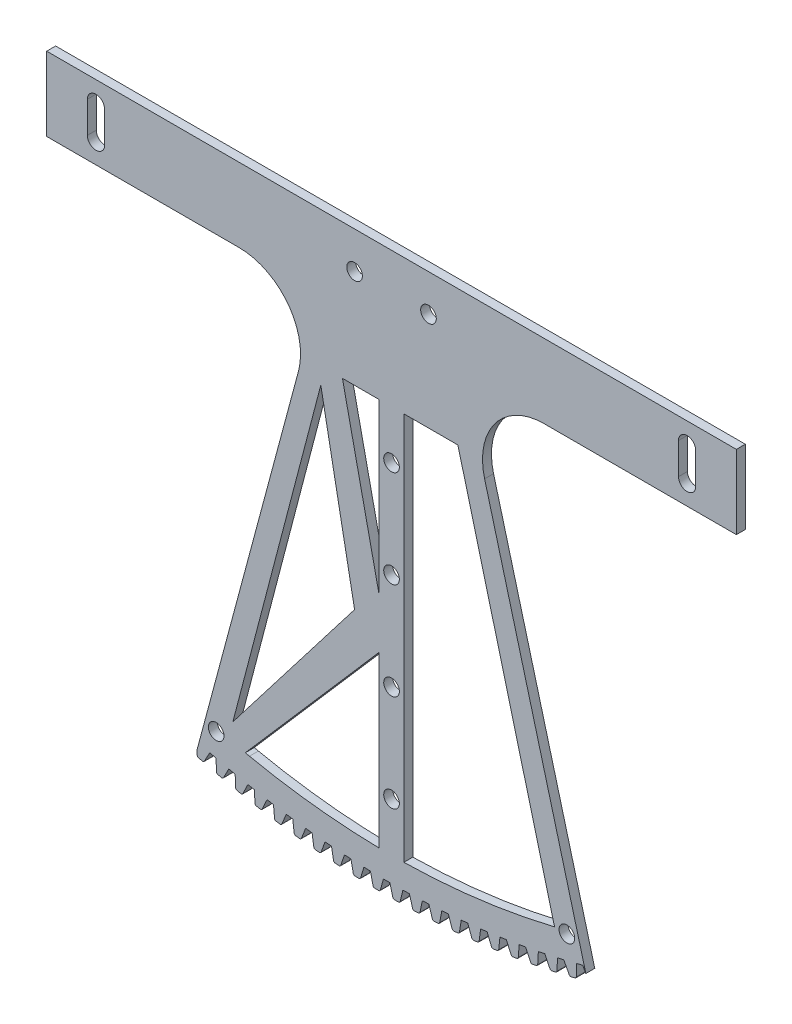
SolidWorks part; units mm, degrees
material "201 Annealed Stainless Steel (SS)"
ref_plane "Front Plane" through (0, 0, 0) normal (0, 0, 1) x (1, 0, 0)
ref_plane "Top Plane" through (0, 0, 0) normal (0, 1, 0) x (1, 0, 0)
ref_plane "Right Plane" through (0, 0, 0) normal (1, 0, 0) x (0, 0, -1)
sketch "Sketch3" plane through (0, 0, 0) normal (0, 0, 1) x (1, 0, 0)
  line L0 (0, 0) -> (0, -304.8) construction
  line L1 (-21.234, -79.2464) -> (-78.888, -294.4142)
  line L2 (21.234, -79.2464) -> (78.888, -294.4142)
  line L4 (-140, -79.56) -> (140, -79.56)
  line L5 (-140, -79.56) -> (-140, -109.56)
  line L6 (-140, -109.56) -> (140, -109.56)
  line L7 (140, -79.56) -> (140, -109.56)
  line L8 (0, -109.56) -> (0, -79.56) construction
  line L9 (-140, -94.56) -> (140, -94.56) construction
  arc A0 (-78.888, -294.4142) -> (78.888, -294.4142) centre (0, 0) ccw
  point P269 (0, -94.56)
  dimension "D1" = 304.8
  dimension "D4" = 79.56
  dimension "D5" = 30
  dimension "D6" = 280
  dimension "D7" = 140
extrude "Boss-Extrude2" add sketch "Sketch3" along normal blind 3.6286 contours L7 L4 L2 L6 | L1 L6 L2 L4 | L1 L4 L2 | L5 L6 L1 L4 | L1 A0 L2 L6
fillet "Fillet1" radius 25 2 edges at (-29.3565, -109.56, 1.8143) (29.3565, -109.56, 1.8143)
sketch "Sketch4" plane through (0, -79.56, 0) normal (0, 1, 0) x (1, 0, 0)
  line L1 (-140, 0) -> (140, 0)
  line L2 (-140, 0) -> (-140, -3.6286)
  line L3 (-140, -3.6286) -> (140, -3.6286)
  line L4 (140, 0) -> (140, -3.6286)
  line L5 (0, -3.6286) -> (0, 0) construction
  line L6 (-140, -1.8143) -> (140, -1.8143) construction
  point P252 (0, -1.8143)
sketch "Sketch5" plane through (0, 0, 0) normal (0, 0, -1) x (-1, 0, 0)
  line L0 (-123.5, -94.56) -> (-123.5, -100.91)
  line L1 (-116.5, -94.56) -> (-116.5, -100.91)
  line L2 (116.5, -94.56) -> (116.5, -88.21)
  line L3 (140, -79.56) -> (-140, -79.56) construction
  line L4 (-120, -88.21) -> (-120, -100.91) construction
  line L5 (0, -79.56) -> (0, -109.56) construction
  line L6 (-116.5, -94.56) -> (-116.5, -88.21)
  line L7 (-123.5, -94.56) -> (-123.5, -88.21)
  line L8 (116.5, -94.56) -> (116.5, -100.91)
  line L9 (123.5, -94.56) -> (123.5, -100.91)
  line L10 (123.5, -94.56) -> (123.5, -88.21)
  line L11 (-140, -79.56) -> (-140, -109.56) construction
  line L12 (120, -88.21) -> (120, -100.91) construction
  arc A1 (-116.5, -88.21) -> (-123.5, -88.21) centre (-120, -88.21) ccw
  arc A2 (-123.5, -100.91) -> (-116.5, -100.91) centre (-120, -100.91) ccw
  arc A3 (123.5, -100.91) -> (116.5, -100.91) centre (120, -100.91) cw
  arc A4 (116.5, -88.21) -> (123.5, -88.21) centre (120, -88.21) cw
  circle A5 centre (-15, -94.56) radius 3.175
  circle A6 centre (15, -94.56) radius 3.175
  dimension "D1" = 16.5
  dimension "D2" = 7
  dimension "D3" = 8.65
  dimension "D5" = 3.5
  dimension "D6" = 15
  dimension "D8" = 6.35
  dimension "D4" = 6.35
  dimension "D7" = 15
sketch "Sketch13" plane through (0, 0, 0) normal (0, 0, -1) x (-1, 0, 0)
  line L0 (0, 0) -> (78.888, -294.4142)
  line L1 (0, 0) -> (-78.888, -294.4142)
  arc A0 (-78.888, -294.4142) -> (78.888, -294.4142) centre (0, 0) ccw
  arc A1 (-78.888, -294.4142) -> (78.888, -294.4142) centre (0, 0) ccw construction
  arc A2 (-78.888, -294.4142) -> (78.888, -294.4142) centre (0, 0) ccw
  circle A3 centre (0, 0) radius 304.8
  dimension "D1" = 609.6
sketch "Sketch14" plane through (0, 0, 0) normal (0, 0, -1) x (-1, 0, 0)
  line L0 (0, 0) -> (80.0203, -298.6399) construction
  line L2 (78.888, -294.4142) -> (78.9109, -297.0369)
  line L3 (78.9109, -297.0369) -> (76.2891, -297.7211)
  line L18 (76.2891, -297.7211) -> (75.0275, -295.4216)
  line L20 (0, 0) -> (-79.2746, -295.8555) construction
  line L32 (78.888, -294.4142) -> (75.0275, -295.4216)
  line L33 (75.0275, -295.4216) -> (78.888, -294.4142)
  line L34 (0, 0) -> (-75.3952, -296.8678) construction
  line L35 (0, 0) -> (-71.5028, -297.8293) construction
  line L36 (0, 0) -> (-67.5982, -298.7397) construction
  line L37 (0, 0) -> (-63.6821, -299.5989) construction
  line L38 (0, 0) -> (-59.755, -300.4068) construction
  line L39 (0, 0) -> (-55.8176, -301.1633) construction
  line L40 (0, 0) -> (-51.8707, -301.8681) construction
  line L41 (0, 0) -> (-47.9149, -302.5212) construction
  line L42 (0, 0) -> (-43.951, -303.1225) construction
  line L43 (0, 0) -> (-39.9794, -303.6718) construction
  line L44 (0, 0) -> (-36.0011, -304.1691) construction
  line L45 (0, 0) -> (-32.0165, -304.6143) construction
  line L46 (0, 0) -> (-28.0265, -305.0073) construction
  line L47 (0, 0) -> (-24.0316, -305.348) construction
  line L48 (0, 0) -> (-20.0327, -305.6364) construction
  line L49 (0, 0) -> (-16.0303, -305.8724) construction
  line L50 (0, 0) -> (-12.0252, -306.0561) construction
  line L51 (0, 0) -> (-8.018, -306.1873) construction
  line L52 (0, 0) -> (-4.0094, -306.266) construction
  line L53 (0, 0) -> (-0.0002, -306.2922) construction
  line L54 (0, 0) -> (4.0091, -306.266) construction
  line L55 (0, 0) -> (8.0176, -306.1873) construction
  line L56 (0, 0) -> (12.0248, -306.0561) construction
  line L57 (0, 0) -> (16.03, -305.8725) construction
  line L58 (0, 0) -> (20.0323, -305.6364) construction
  line L59 (0, 0) -> (24.0313, -305.348) construction
  line L60 (0, 0) -> (28.0261, -305.0073) construction
  line L61 (0, 0) -> (32.0162, -304.6143) construction
  line L62 (0, 0) -> (36.0007, -304.1691) construction
  line L63 (0, 0) -> (39.9791, -303.6719) construction
  line L64 (0, 0) -> (43.9506, -303.1225) construction
  line L65 (0, 0) -> (47.9146, -302.5213) construction
  line L66 (0, 0) -> (51.8704, -301.8682) construction
  line L67 (0, 0) -> (55.8173, -301.1633) construction
  line L68 (0, 0) -> (59.7546, -300.4069) construction
  line L69 (0, 0) -> (63.6817, -299.599) construction
  line L70 (0, 0) -> (67.5979, -298.7398) construction
  line L71 (0, 0) -> (71.5025, -297.8293) construction
  line L72 (0, 0) -> (75.3948, -296.8679) construction
  line L73 (0, 0) -> (-79.2746, -295.8555) construction
  line L74 (0, 0) -> (-75.3952, -296.8678) construction
  line L137 (37.789, -141.0305) -> (78.888, -294.4142) construction
  line L138 (-140, -79.56) -> (-140, -109.56)
  line L139 (-140, -109.56) -> (-61.9371, -109.56)
  line L140 (-37.789, -141.0305) -> (-78.888, -294.4142)
  line L141 (78.888, -294.4142) -> (37.789, -141.0305)
  line L142 (61.9371, -109.56) -> (140, -109.56)
  line L143 (140, -109.56) -> (140, -79.56)
  line L144 (140, -79.56) -> (-140, -79.56)
  line L145 (-140, -79.56) -> (-140, -109.56)
  line L146 (-140, -109.56) -> (-61.9371, -109.56)
  line L147 (-37.789, -141.0305) -> (-78.888, -294.4142)
  line L149 (61.9371, -109.56) -> (140, -109.56)
  line L150 (140, -109.56) -> (140, -79.56)
  line L151 (140, -79.56) -> (-140, -79.56)
  circle A0 centre (0, 0) radius 307.34
  circle A1 centre (0, 0) radius 302.26
  arc A3 (-37.789, -141.0305) -> (-61.9371, -109.56) centre (-61.9371, -134.56) ccw
  arc A5 (61.9371, -109.56) -> (37.789, -141.0305) centre (61.9371, -134.56) ccw
  arc A6 (-37.789, -141.0305) -> (-61.9371, -109.56) centre (-61.9371, -134.56) ccw
  arc A8 (61.9371, -109.56) -> (37.789, -141.0305) centre (61.9371, -134.56) ccw
  arc A11 (-78.888, -294.4142) -> (78.888, -294.4142) centre (0, 0) ccw
  arc A12 (-78.888, -294.4142) -> (78.888, -294.4142) centre (0, 0) ccw
  dimension "D5" = 614.68
  dimension "D6" = 30
  dimension "D7" = 40
  dimension "D4" = 604.52
  dimension "D1" = 14.5
  dimension "D3" = 14.5
  dimension "D8" = 0.75
  dimension "D9" = 306.2922
  dimension "D10" = 0.75
  dimension "D2" = 0
extrude "Boss-Extrude4" add sketch "Sketch14" against normal up to surface (3.6286 mm away) up to face at (0, -146.6727, 3.6286)
sketch "Sketch15" plane through (0, 0, 0) normal (1, 0, 0) x (0, 0, -1)
  line L0 (0, 0) -> (-23.3364, 0) construction
sketch "Sketch16" plane through (0, 0, 0) normal (0, 0, -1) x (-1, 0, 0)
  line L0 (75.0275, -295.4216) -> (73.7653, -293.1208)
  line L1 (73.7653, -293.1208) -> (71.1999, -293.7544)
  line L2 (71.1999, -293.7544) -> (71.1541, -296.3784)
  line L3 (0, 0) -> (71.5025, -297.8293) construction
  line L4 (0, 0) -> (75.3948, -296.8679) construction
  circle A0 centre (0, 0) radius 302.26 construction
  arc A1 (-78.888, -294.4142) -> (78.888, -294.4142) centre (0, 0) ccw construction
  dimension "D1" = 14.5
  dimension "D2" = 14.5
extrude "Cut-Extrude2" cut sketch "Sketch16" against normal through all and the other way through all
fillet "Fillet2" radius 0.7 2 edges at (-76.2891, -297.7211, 1.8143) (-78.9109, -297.0369, 1.8143)
pattern_circular "CirPattern8" count 20 every 1.5 about axis through (0, 0, 0) along (0, 0, 1) of "Cut-Extrude2", "Boss-Extrude4", "Fillet2"
extrude "Cut-Extrude3" cut sketch "Sketch5" against normal through all
sketch "Sketch17" plane through (0, 0, 0) normal (0, 0, -1) x (-1, 0, 0)
  line L0 (0, -79.56) -> (0, -134.56) construction
  line L1 (140, -79.56) -> (-140, -79.56) construction
  line L2 (-61.9371, -109.56) -> (61.9371, -109.56) construction
  line L3 (-36.9371, -134.56) -> (-26.9371, -134.56) construction
  line L4 (-36.9371, -134.56) -> (-26.9371, -134.56) construction
  line L5 (-26.9371, -134.56) -> (-66.1944, -284.3612) construction
  line L6 (-66.1944, -284.3612) -> (-76.1944, -284.3612) construction
  line L7 (0, -292.2593) -> (5, -292.2593) construction
  line L8 (-37.789, -141.0305) -> (-78.888, -294.4142) construction
  line L9 (0, -134.56) -> (-5, -134.56) construction
  line L10 (0, -134.56) -> (5, -134.56) construction
  line L11 (26.9371, -134.56) -> (36.9371, -134.56) construction
  line L12 (-5, -134.56) -> (-5, -292.2593) construction
  line L13 (36.9371, -134.56) -> (26.9371, -134.56) construction
  line L14 (26.9371, -134.56) -> (66.1944, -284.3612) construction
  line L15 (66.1944, -284.3612) -> (76.1944, -284.3612) construction
  line L16 (37.789, -141.0305) -> (78.888, -294.4142) construction
  line L17 (0.6571, -302.2593) -> (-3.5916, -302.2593) construction
  line L18 (-5, -134.56) -> (5, -134.56) construction
  line L19 (-3.5916, -292.2593) -> (-5, -292.2593) construction
  line L20 (5, -134.56) -> (5, -292.2593) construction
  line L21 (-3.5916, -302.2593) -> (-3.5916, -292.2593) construction
  line L22 (0, -193.6972) -> (0, -233.1221) construction
  line L23 (64.4199, -277.5899) -> (15, -213.4096)
  line L24 (-66.1944, -284.3612) -> (-68.6354, -294.3612) construction
  line L25 (-67.3487, -294.6613) -> (-69.9221, -294.0612) construction
  line L26 (71.1999, -293.7544) -> (66.067, -294.9513) construction
  line L27 (66.1944, -284.3612) -> (68.6335, -294.3529) construction
  line L28 (26.9371, -134.56) -> (66.1944, -284.3612)
  line L29 (26.9371, -134.56) -> (5, -134.56)
  line L30 (5, -134.56) -> (5, -292.2593)
  line L31 (-66.1944, -284.3612) -> (-26.9371, -134.56)
  line L32 (-26.9371, -134.56) -> (-5, -134.56)
  line L33 (-5, -134.56) -> (-5, -292.2593)
  line L34 (15, -213.4096) -> (28.7117, -141.3313)
  line L35 (66.1944, -284.3612) -> (57.6779, -286.2946)
  line L36 (66.1944, -284.3612) -> (64.4199, -277.5899) construction
  line L37 (5, -223.4096) -> (59.3729, -285.9321)
  line L41 (26.9371, -134.56) -> (28.7117, -141.3313) construction
  line L42 (26.9371, -134.56) -> (19.9371, -134.56) construction
  line L44 (28.7117, -141.3313) -> (26.9371, -134.56) construction
  line L47 (5, -203.4096) -> (19.9371, -134.56)
  circle A0 centre (0, -272.5469) radius 3.175
  arc A1 (61.9371, -109.56) -> (37.789, -141.0305) centre (61.9371, -134.56) ccw construction
  arc A2 (-37.789, -141.0305) -> (-61.9371, -109.56) centre (-61.9371, -134.56) ccw construction
  arc A3 (-66.1944, -284.3612) -> (-5, -292.2593) centre (0, -12.5018) ccw
  arc A4 (5, -292.2593) -> (66.1944, -284.3612) centre (0, -12.5018) ccw
  circle A5 centre (0, -233.1221) radius 3.175
  circle A6 centre (0, -193.6972) radius 3.175
  circle A7 centre (0, -154.2724) radius 3.175
  circle A8 centre (-71.1944, -284.3612) radius 3.175
  circle A9 centre (71.1944, -284.3612) radius 3.175
  arc A13 (19.9371, -134.56) -> (28.7117, -141.3313) centre (26.9371, -134.56) ccw construction
  arc A14 (19.9371, -134.56) -> (28.7117, -141.3313) centre (26.9371, -134.56) ccw construction
  arc A15 (-59.3729, -285.9321) -> (-64.4199, -277.5899) centre (-66.1944, -284.3612) ccw construction
  arc A16 (-64.4199, -277.5899) -> (-59.3729, -285.9321) centre (-66.1944, -284.3612) cw
  arc A17 (-5, -203.4096) -> (-5, -223.4096) centre (-5, -213.4096) ccw construction
  arc A18 (-28.7117, -141.3313) -> (-19.9371, -134.56) centre (-26.9371, -134.56) ccw construction
  arc A19 (5, -223.4096) -> (5, -203.4096) centre (5, -213.4096) ccw construction
  arc A20 (64.4199, -277.5899) -> (59.3729, -285.9321) centre (66.1944, -284.3612) ccw construction
  dimension "D13" = 6.35
  dimension "D14" = 6.35
  dimension "D15" = 10
  dimension "D16" = 7
  dimension "D17" = 7
  dimension "D20" = 7
  dimension "D21" = 10
  dimension "D22" = 7
  dimension "D18" = 7
  dimension "D1" = 10
  dimension "D2" = 5
  dimension "D3" = 10
  dimension "D4" = 10
  dimension "D5" = 5
  dimension "D6" = 5
  dimension "D7" = 10
  dimension "D8" = 10
  dimension "D9" = 5
  dimension "D10" = 10
  dimension "D11" = 157.6993
  dimension "D12" = 10
extrude "Cut-Extrude4" cut sketch "Sketch17" against normal through all
equation "\"D7@Sketch3\"=\"D6@Sketch3\"/2"
